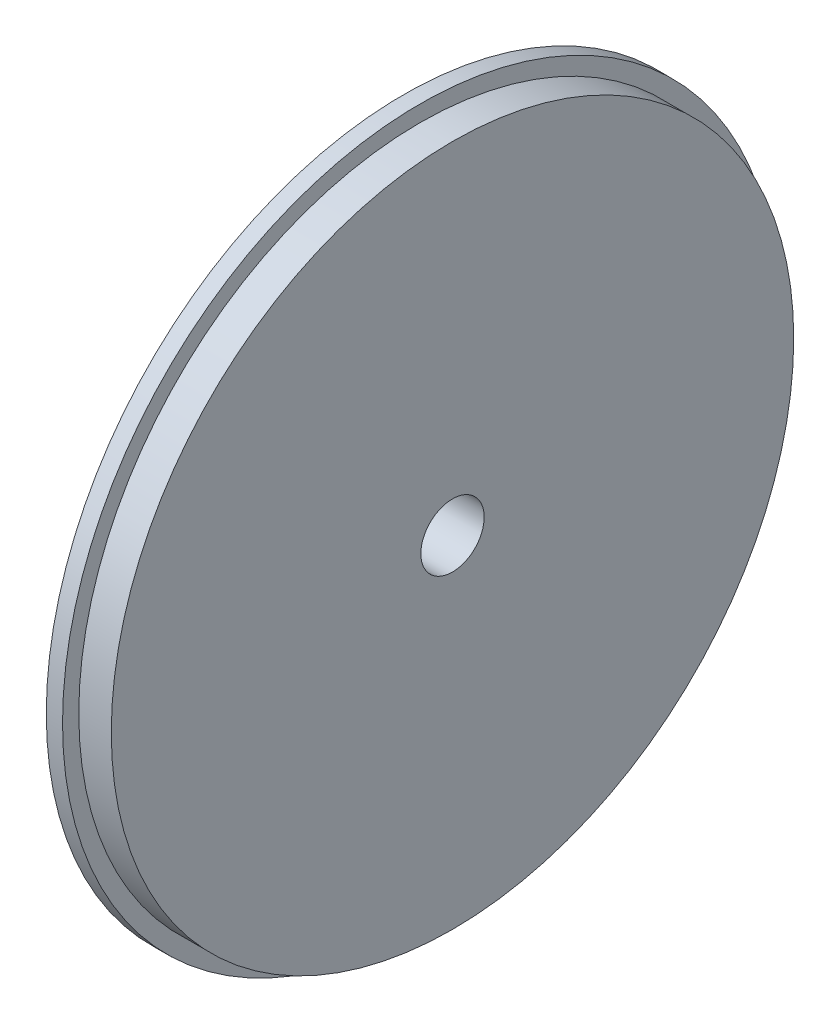
SolidWorks part; units mm, degrees
ref_plane "Front Plane" through (0, 0, 0) normal (0, 0, 1) x (1, 0, 0)
ref_plane "Top Plane" through (0, 0, 0) normal (0, 1, 0) x (1, 0, 0)
ref_plane "Right Plane" through (0, 0, 0) normal (1, 0, 0) x (0, 0, -1)
sketch "Sketch1" plane through (0, 0, 0) normal (0, 0, 1) x (1, 0, 0)
  line L0 (-0.75, 11) -> (-0.25, 11)
  line L1 (-0.75, 11) -> (0.75, 11) construction
  line L2 (-0.75, 11) -> (-0.75, 0) construction
  line L3 (-0.75, 0) -> (0.75, 0) construction
  line L4 (0.75, 11) -> (0.75, 0) construction
  line L5 (-0.75, 0.975) -> (0.75, 0.975)
  line L6 (-0.75, 0.975) -> (-0.75, 11)
  line L8 (0.75, 0.975) -> (0.75, 10.5)
  line L9 (-0.25, 11) -> (-0.25, 10.5)
  line L10 (-0.25, 10.5) -> (0.75, 10.5)
  dimension "D1" = 11
  dimension "D2" = 1.5
  dimension "D3" = 0.975
  dimension "D4" = 10.5
  dimension "D5" = 0.5
revolve "Revolve1" add sketch "Sketch1" angle 360 about L3
